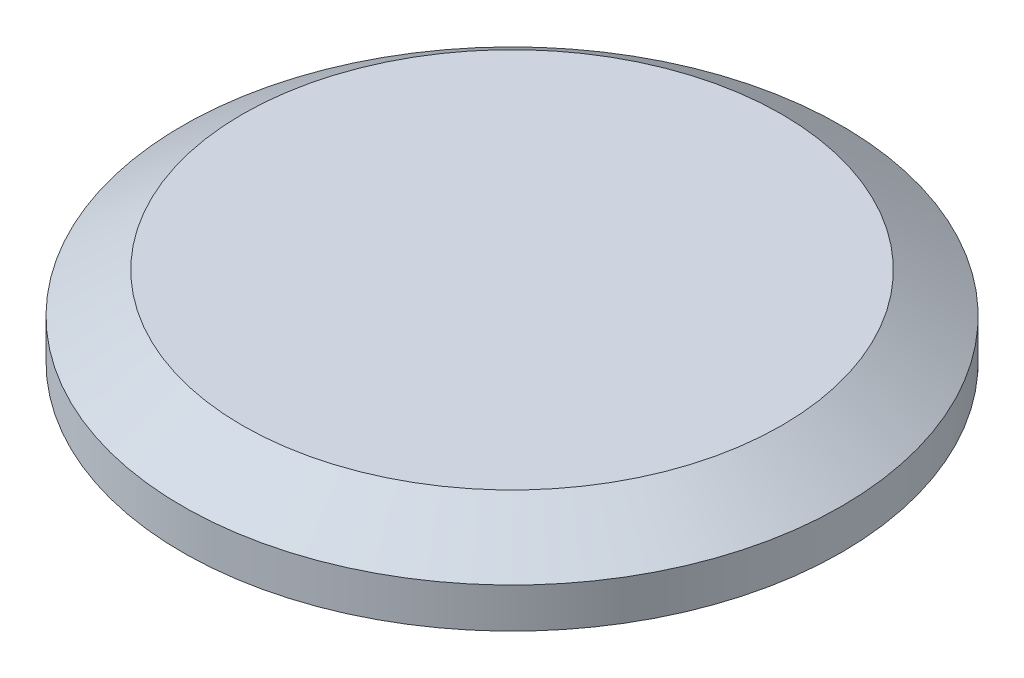
SolidWorks part; units mm, degrees
ref_plane "Спереди" through (0, 0, 0) normal (0, 0, 1) x (1, 0, 0)
ref_plane "Сверху" through (0, 0, 0) normal (0, 1, 0) x (1, 0, 0)
ref_plane "Справа" through (0, 0, 0) normal (1, 0, 0) x (0, 0, -1)
sketch "Эскиз1" plane through (0, 0, 0) normal (0, 0, 1) x (1, 0, 0)
  line L0 (0, 0) -> (-3, 0)
  line L1 (-3, 0) -> (-3, 9)
  line L2 (-3, 9) -> (-13.5, 9)
  line L3 (-13.5, 9) -> (-16.5, 7)
  line L4 (-16.5, 7) -> (-16.5, 9)
  line L5 (-16.5, 9) -> (-13.5, 11)
  line L6 (-13.5, 11) -> (0, 11)
  line L7 (0, 0) -> (0, 11)
  point P3 (0, 0)
  dimension "D1" = 3
  dimension "D2" = 11
  dimension "D3" = 2
  dimension "D4" = 2
  dimension "D5" = 13.5
  dimension "D6" = 4
  dimension "D7" = 16.5
revolve "Повернуть1" add sketch "Эскиз1" angle 360 about L7
